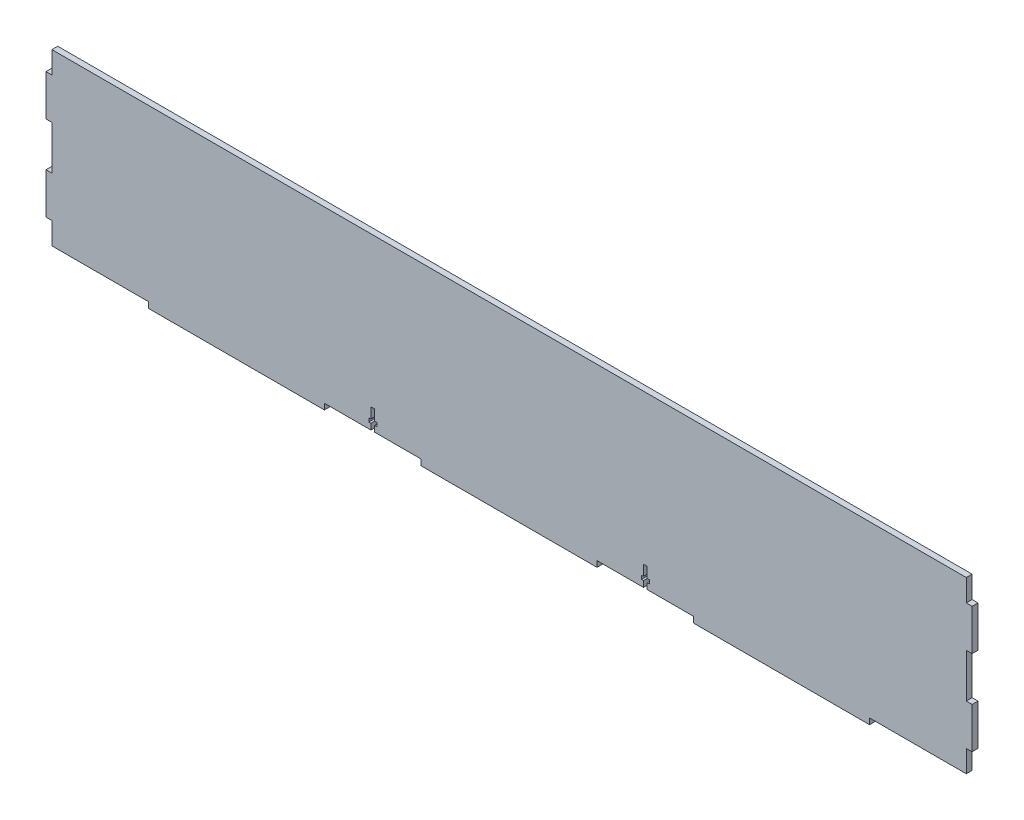
SolidWorks part; units mm, degrees
ref_plane "Alzado" through (0, 0, 0) normal (0, 0, 1) x (1, 0, 0)
ref_plane "Planta" through (0, 0, 0) normal (0, 1, 0) x (1, 0, 0)
ref_plane "Vista lateral" through (0, 0, 0) normal (1, 0, 0) x (0, 0, -1)
sketch "Croquis1" plane through (0, 0, 0) normal (0, 0, 1) x (1, 0, 0)
  line L0 (390, 0) -> (390, -116.2557) construction
  line L1 (0, 0) -> (780, 0)
  line L2 (0, 0) -> (0, 145)
  line L3 (0, 145) -> (780, 145)
  line L4 (780, 0) -> (780, 145)
  line L5 (0, 72.5) -> (-47.1531, 72.5) construction
  line L6 (0, 53.75) -> (-5, 53.75)
  line L7 (0, 126.25) -> (-5, 126.25)
  line L8 (0, 126.25) -> (0, 91.25)
  line L9 (0, 91.25) -> (-5, 91.25)
  line L10 (-5, 126.25) -> (-5, 91.25)
  line L11 (-5, 18.75) -> (-5, 53.75)
  line L12 (0, 18.75) -> (-5, 18.75)
  line L13 (0, 18.75) -> (0, 53.75)
  line L14 (780, 18.75) -> (780, 53.75)
  line L15 (780, 18.75) -> (785, 18.75)
  line L16 (785, 18.75) -> (785, 53.75)
  line L17 (780, 53.75) -> (785, 53.75)
  line L18 (780, 91.25) -> (785, 91.25)
  line L19 (785, 126.25) -> (785, 91.25)
  line L20 (780, 126.25) -> (785, 126.25)
  line L21 (780, 126.25) -> (780, 91.25)
  line L22 (390, 0) -> (315, 0)
  line L27 (82.5, 0) -> (232.5, 0)
  line L28 (82.5, 0) -> (82.5, -5)
  line L29 (82.5, -5) -> (232.5, -5)
  line L30 (232.5, 0) -> (232.5, -5)
  line L31 (315, 0) -> (315, -5)
  line L36 (315, -5) -> (465, -5)
  line L37 (465, -5) -> (465, 0)
  line L38 (465, 0) -> (390, 0)
  line L39 (697.5, -5) -> (547.5, -5)
  line L40 (547.5, 0) -> (547.5, -5)
  line L41 (697.5, 0) -> (547.5, 0)
  line L42 (697.5, 0) -> (697.5, -5)
  dimension "D1" = 780
  dimension "D2" = 145
  dimension "D3" = 18.75
  dimension "D4" = 35
  dimension "D5" = 5
  dimension "D6" = 75
  dimension "D7" = 150
  dimension "D8" = 82.5
  dimension "D9" = 150
  dimension "D10" = 5
  dimension "D11" = 5
extrude "Saliente-Extruir1" add sketch "Croquis1" along normal blind 5 contours L1 L4 L3 L2 | L42 L1 L40 L39 | L36 L37 L1 L31 | L30 L1 L28 L29 | L12 L2 L6 L11 | L16 L17 L14 L15 | L19 L18 L21 L20 | L10 L9 L8 L7
sketch "Croquis2" plane through (0, 0, 5) normal (0, 0, 1) x (1, 0, 0)
  line L0 (273.75, 0) -> (273.75, 79.0587) construction
  line L1 (232.5, 0) -> (315, 0) construction
  line L2 (390, -5) -> (390, 84.2504) construction
  line L3 (315, -5) -> (465, -5) construction
  line L4 (275.35, 0) -> (272.15, 0)
  line L5 (272.15, 0) -> (272.15, 5)
  line L6 (272.15, 5) -> (270.35, 5)
  line L7 (270.35, 5) -> (270.35, 8.2)
  line L8 (270.35, 8.2) -> (272.15, 8.2)
  line L9 (272.15, 8.2) -> (272.15, 17.2)
  line L10 (272.15, 17.2) -> (275.35, 17.2)
  line L11 (275.35, 8.2) -> (275.35, 17.2)
  line L12 (277.15, 8.2) -> (275.35, 8.2)
  line L13 (277.15, 5) -> (277.15, 8.2)
  line L14 (275.35, 5) -> (277.15, 5)
  line L15 (275.35, 0) -> (275.35, 5)
  line L16 (507.85, 8.2) -> (507.85, 17.2)
  line L17 (509.65, 8.2) -> (507.85, 8.2)
  line L18 (509.65, 5) -> (509.65, 8.2)
  line L19 (507.85, 5) -> (509.65, 5)
  line L20 (507.85, 0) -> (507.85, 5)
  line L21 (504.65, 0) -> (507.85, 0)
  line L22 (504.65, 0) -> (504.65, 5)
  line L23 (504.65, 5) -> (502.85, 5)
  line L24 (502.85, 5) -> (502.85, 8.2)
  line L25 (502.85, 8.2) -> (504.65, 8.2)
  line L26 (504.65, 8.2) -> (504.65, 17.2)
  line L27 (507.85, 17.2) -> (504.65, 17.2)
  point P16 (273.75, 17.2)
  dimension "D1" = 1.6
  dimension "D2" = 5
  dimension "D3" = 1.8
  dimension "D4" = 3.2
  dimension "D5" = 1.8
  dimension "D6" = 9
extrude "Cortar-Extruir1" cut sketch "Croquis2" against normal blind 10 contours L10 L11 L12 L13 L14 L15 L4 L5 L6 L7 L8 L9 | L16 L27 L26 L25 L24 L23 L22 L21 L20 L19 L18 L17
